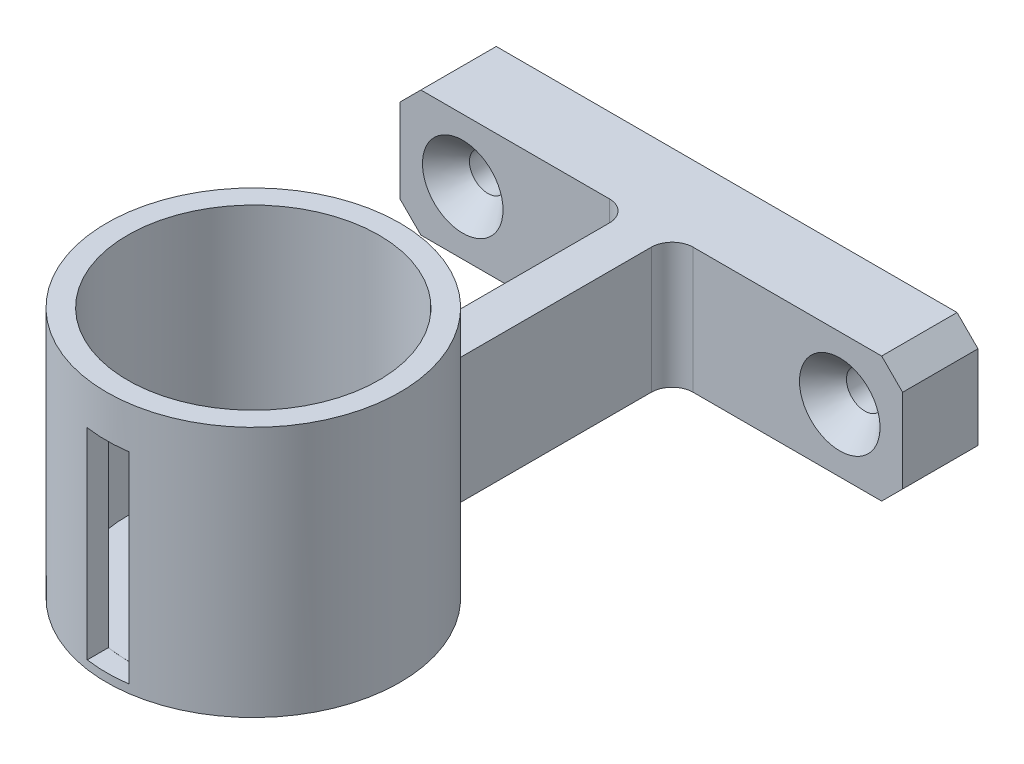
SolidWorks part; units mm, degrees
ref_plane "Front Plane" through (0, 0, 0) normal (0, 0, 1) x (1, 0, 0)
ref_plane "Top Plane" through (0, 0, 0) normal (0, 1, 0) x (1, 0, 0)
ref_plane "Right Plane" through (0, 0, 0) normal (1, 0, 0) x (0, 0, -1)
sketch "Sketch1" plane through (0, 0, 0) normal (0, 0, 1) x (1, 0, 0)
  line L0 (7.5, -7.5) -> (0, -7.5) construction
  line L1 (0, 0) -> (60, 0)
  line L2 (0, 0) -> (0, -15)
  line L3 (0, -15) -> (60, -15)
  line L4 (60, 0) -> (60, -15)
  line L5 (30, 0) -> (30, -15) construction
  circle A0 centre (7.5, -7.5) radius 2.2
  circle A1 centre (52.5, -7.5) radius 2.2
  dimension "D1" = 4.4
  dimension "D2" = 7.5
  dimension "D3" = 15
  dimension "D4" = 60
extrude "Boss-Extrude1" add sketch "Sketch1" along normal blind 9
ref_plane "Plane1" through (7.5, 0, 0) normal (1, 0, 0) x (0, 0, -1)
sketch "Sketch3" plane through (7.5, 0, 0) normal (1, 0, 0) x (0, 0, -1)
  line L0 (-9, -7.5) -> (-6, -7.5)
  line L1 (-9, -15) -> (-9, 0) construction
  line L2 (-6, -7.5) -> (-6, -9.7)
  line L3 (-6, -9.7) -> (-9, -12.3079)
  line L4 (-9, -12.3079) -> (-9, -7.5)
  dimension "D1" = 3
  dimension "D2" = 2.2
  dimension "D3" = 131
revolve "Cut-Revolve1" cut sketch "Sketch3" angle 360 about L0
ref_plane "Plane2" through (30, 0, 0) normal (1, 0, 0) x (0, 0, -1)
mirror "Mirror1" about plane through (30, 0, 0) normal (1, 0, 0) of "Cut-Revolve1"
sketch "Sketch4" plane through (0, 0, 9) normal (0, 0, 1) x (1, 0, 0)
  line L0 (30, 0) -> (30, -15) construction
  line L1 (60, 0) -> (0, 0) construction
  line L2 (0, -15) -> (60, -15) construction
  line L4 (27.5, 0) -> (32.5, 0)
  line L5 (27.5, 0) -> (27.5, -15)
  line L6 (27.5, -15) -> (32.5, -15)
  line L7 (32.5, 0) -> (32.5, -15)
  line L8 (27.5, 0) -> (32.5, -15) construction
  line L9 (27.5, -15) -> (32.5, 0) construction
  point P6 (30, -7.5)
  dimension "D1" = 5
extrude "Boss-Extrude2" add sketch "Sketch4" along normal offset from surface (51 mm away) 60 up to face at (30, -7.5, 0)
sketch "Sketch5" plane through (0, -15, 0) normal (0, -1, 0) x (1, 0, 0)
  line L0 (30, 60) -> (30, 56.5) construction
  line L1 (27.5, 60) -> (32.5, 60) construction
  circle A0 centre (30, 56.5) radius 17.5
  dimension "D2" = 35
  dimension "D1" = 3.5
extrude "Boss-Extrude3" add sketch "Sketch5" against normal blind 30
sketch "Sketch6" plane through (0, -15, 0) normal (0, -1, 0) x (1, 0, 0)
  circle A0 centre (30, 56.5) radius 15
  dimension "D1" = 30
extrude "Cut-Extrude1" cut sketch "Sketch6" against normal through all
fillet "Fillet1" radius 2.5 4 edges at (27.5, -7.5, 39.1795) (32.5, -7.5, 39.1795) (32.5, -7.5, 9) (27.5, -7.5, 9)
chamfer "Chamfer1" distance 2.5 angle 45 4 edges at (60, -15, 4.5) (60, 0, 4.5) (0, 0, 4.5) (0, -15, 4.5)
sketch "Sketch7" plane through (0, -15, 0) normal (0, -1, 0) x (1, 0, 0)
  circle A0 centre (30, 56.5) radius 15
  circle A1 centre (30, 56.5) radius 15 construction
  circle A2 centre (30, 56.5) radius 1.5
  dimension "D1" = 3
extrude "Boss-Extrude4" add sketch "Sketch7" against normal blind 1 separate body
sketch "Sketch8" plane through (0, -14, 0) normal (0, -1, 0) x (1, 0, 0)
  line L0 (32.5, 37.1351) -> (32.5, 11.5) construction
  line L1 (32.5, 71.2902) -> (27.5, 71.2902)
  line L2 (32.5, 71.2902) -> (32.5, 76.7902)
  line L3 (32.5, 76.7902) -> (27.5, 76.7902)
  line L4 (27.5, 71.2902) -> (27.5, 76.7902)
  line L5 (27.5, 37.1351) -> (27.5, 11.5) construction
  circle A0 centre (30, 56.5) radius 15 construction
  dimension "D1" = 5.5
extrude "Cut-Extrude2" cut sketch "Sketch8" against normal offset from surface (24 mm away) 5 up to face at (30, 15, 41.5)
